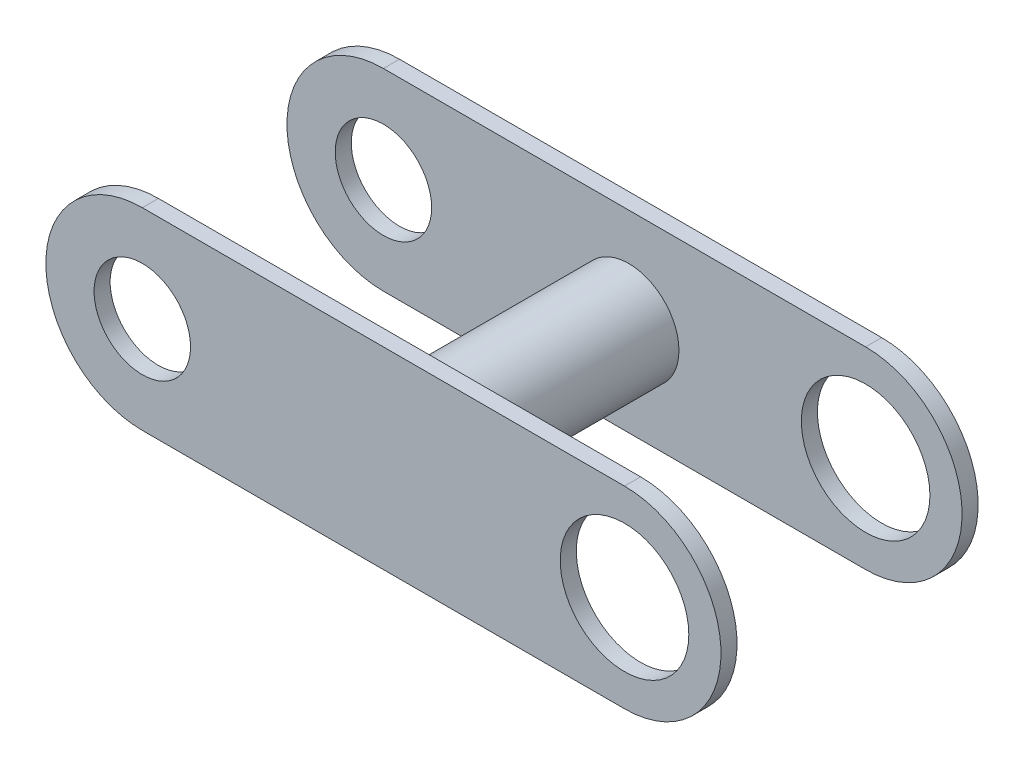
SolidWorks part; units mm, degrees
ref_plane "前视基准面" through (0, 0, 0) normal (0, 0, 1) x (1, 0, 0)
ref_plane "上视基准面" through (0, 0, 0) normal (0, 1, 0) x (1, 0, 0)
ref_plane "右视基准面" through (0, 0, 0) normal (1, 0, 0) x (0, 0, -1)
sketch "草图1" plane through (0, 0, 0) normal (0, 0, 1) x (1, 0, 0)
  line L0 (-31.5987, 0) -> (118.4013, 0) construction
  line L1 (-31.5987, 30) -> (118.4013, 30)
  line L2 (-31.5987, -30) -> (118.4013, -30)
  arc A0 (-31.5987, 30) -> (-31.5987, -30) centre (-31.5987, 0) ccw
  arc A1 (118.4013, -30) -> (118.4013, 30) centre (118.4013, 0) ccw
  circle A2 centre (-31.5987, 0) radius 15
  circle A3 centre (118.4013, 0) radius 20
  point P3 (43.4013, 0)
  dimension "D3" = 30
  dimension "D4" = 40
  dimension "D1" = 150
  dimension "D2" = 60
extrude "凸台-拉伸1" add sketch "草图1" along normal blind 5
sketch "草图2" plane through (0, 0, 5) normal (0, 0, 1) x (1, 0, 0)
  circle A0 centre (44.7134, 0) radius 15.6199
extrude "凸台-拉伸2" add sketch "草图2" along normal blind 70
pattern_linear "阵列(线性)1" count 2 spacing 75 along (0, 0, 1) of "凸台-拉伸1"
